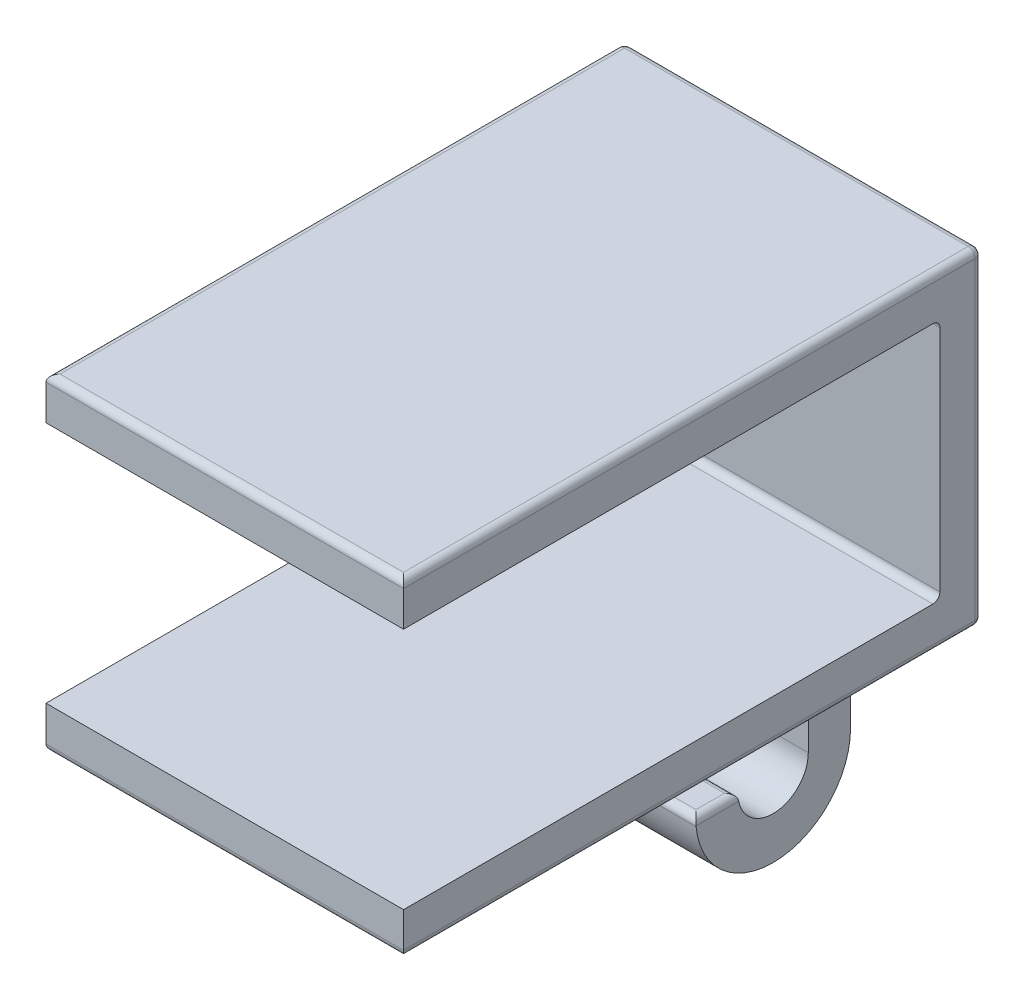
SolidWorks part; units mm, degrees
ref_plane "Front Plane" through (0, 0, 0) normal (0, 0, 1) x (1, 0, 0)
ref_plane "Top Plane" through (0, 0, 0) normal (0, 1, 0) x (1, 0, 0)
ref_plane "Right Plane" through (0, 0, 0) normal (1, 0, 0) x (0, 0, -1)
sketch "Sketch1" plane through (0, 0, 0) normal (1, 0, 0) x (0, 0, -1)
  line L0 (0, 0) -> (38.1, 0)
  line L1 (38.1, 0) -> (38.1, -17.25)
  line L2 (38.1, -17.25) -> (0, -17.25)
  line L3 (0, -17.25) -> (0, -20.25)
  line L4 (0, -20.25) -> (41.1, -20.25)
  line L5 (41.1, -20.25) -> (41.1, 3)
  line L6 (41.1, 3) -> (0, 3)
  line L7 (0, 3) -> (0, 0)
  dimension "D5" = 17.25
  dimension "D1" = 3
  dimension "D2" = 3
  dimension "D3" = 3
  dimension "D4" = 38.1
extrude "Boss-Extrude1" add sketch "Sketch1" along normal blind 25.4
sketch "Sketch7" plane through (0, 0, 0) normal (-1, 0, 0) x (0, 0, 1)
  line L0 (-38.1, -20.25) -> (-38.1, -28.3363)
  line L2 (-27.1, -28.3363) -> (-30.1, -28.3363)
  line L3 (-35.1, -28.3218) -> (-35.1, -20.25)
  line L4 (0, -20.25) -> (-41.1, -20.25) construction
  line L5 (-35.1, -20.25) -> (-38.1, -20.25)
  arc A0 (-38.1, -28.3363) -> (-27.1, -28.3363) centre (-32.6, -28.3363) ccw
  arc A1 (-30.1, -28.3363) -> (-35.1, -28.3218) centre (-32.6, -28.3218) cw
  dimension "D2" = 5.5
  dimension "D1" = 3
  dimension "D3" = 3
extrude "Boss-Extrude3" add sketch "Sketch7" against normal blind 25.4
sketch "Sketch8" plane through (0, 0, 0) normal (-1, 0, 0) x (0, 0, 1)
  line L0 (-35.1, -20.25) -> (-38.1, -20.25)
  line L1 (-38.1, -20.25) -> (-38.1, -28.3363)
  line L2 (-35.1, -20.25) -> (-35.1, -28.3218)
  line L3 (-35.1, -28.3218) -> (-35.1, -20.25) construction
  line L4 (-30.1, -28.3363) -> (-27.1, -28.3363)
  arc A0 (-35.1, -28.3218) -> (-30.1, -28.3363) centre (-32.6, -28.3218) ccw construction
  arc A1 (-38.1, -28.3363) -> (-27.1, -28.3363) centre (-32.6, -28.3363) ccw
  arc A2 (-30.1, -28.3363) -> (-35.1, -28.3218) centre (-32.6, -28.3218) cw
extrude "Cut-Extrude5" cut sketch "Sketch8" against normal blind 6.35
sketch "Sketch9" plane through (25.4, 0, 0) normal (1, 0, 0) x (0, 0, -1)
  line L0 (35.1, -20.25) -> (38.1, -20.25)
  line L1 (38.1, -20.25) -> (38.1, -28.3363)
  line L2 (35.1, -20.25) -> (35.1, -28.3218)
  line L3 (27.1, -28.3363) -> (30.1, -28.3363)
  arc A0 (38.1, -28.3363) -> (27.1, -28.3363) centre (32.6, -28.3363) cw
  arc A1 (35.1, -28.3218) -> (30.1, -28.3363) centre (32.6, -28.3218) cw
extrude "Cut-Extrude6" cut sketch "Sketch9" against normal blind 6.35
fillet "Fillet1" radius 2.5 2 edges at (12.7, -20.25, -38.1) (12.7, -20.25, -35.1)
fillet "Fillet2" radius 2.5 2 edges at (6.35, -20.25, -36.6) (19.05, -20.25, -36.6)
fillet "Fillet3" radius 0.5 10 edges at (12.7, 3, 0) (12.7, -20.25, 0) (25.4, -20.25, -20.55) (25.4, -8.625, -41.1) (25.4, 3, -20.55) (12.7, 3, -41.1) (0, 3, -20.55) (0, -8.625, -41.1) (0, -20.25, -20.55) (12.7, -20.25, -41.1)
fillet "Fillet4" radius 0.5 4 edges at (19.05, -28.3363, -28.6) (6.35, -28.3363, -28.6) (12.7, -28.3363, -30.1) (12.7, -28.3363, -27.1)
fillet "Fillet5" radius 0.5 2 edges at (12.7, 0, -38.1) (12.7, -17.25, -38.1)
